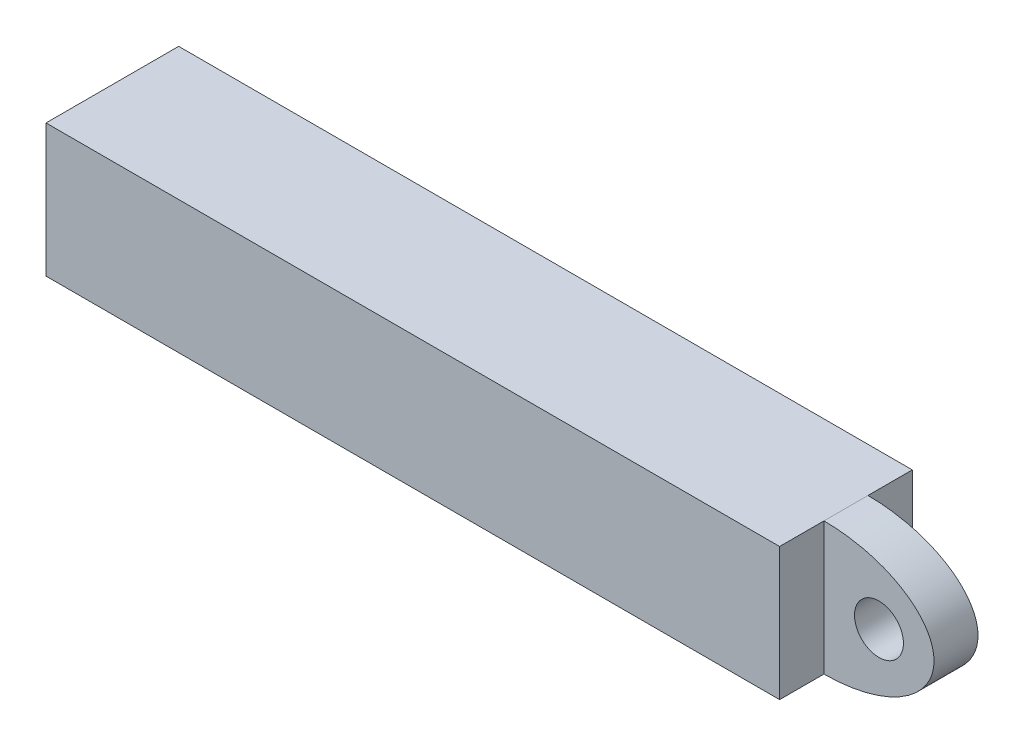
SolidWorks part; units mm, degrees
ref_plane "Front Plane" through (0, 0, 0) normal (0, 0, 1) x (1, 0, 0)
ref_plane "Top Plane" through (0, 0, 0) normal (0, 1, 0) x (1, 0, 0)
ref_plane "Right Plane" through (0, 0, 0) normal (1, 0, 0) x (0, 0, -1)
sketch "Sketch1" plane through (0, 0, 0) normal (1, 0, 0) x (0, 0, -1)
  line L1 (34.45, -34.45) -> (-34.45, -34.45)
  line L2 (34.45, -34.45) -> (34.45, 34.45)
  line L3 (34.45, 34.45) -> (-34.45, 34.45)
  line L4 (-34.45, -34.45) -> (-34.45, 34.45)
  line L5 (34.45, -34.45) -> (-34.45, 34.45) construction
  line L6 (34.45, 34.45) -> (-34.45, -34.45) construction
  point P0 (0, 0)
  dimension "D1" = 68.9
extrude "Boss-Extrude1" add sketch "Sketch1" along normal blind 381
sketch "Sketch2" plane through (0, 0, 0) normal (0, 0, 1) x (1, 0, 0)
  line L1 (381, 34.45) -> (381, -34.45) construction
  line L2 (381, 0) -> (438.15, 0) construction
  line L3 (381, 34.45) -> (381, -34.45)
  circle A1 centre (409.575, 0) radius 12.7
  ellipse E0 centre (381, 0) end of major axis (438.15, 0) minor radius 34.45 (381, -34.45) -> (381, 34.45) ccw
  point P11 (409.575, 0)
  dimension "D1" = 25.4
  dimension "D2" = 57.15
extrude "Boss-Extrude2" add sketch "Sketch2" along normal mid plane 22.86
